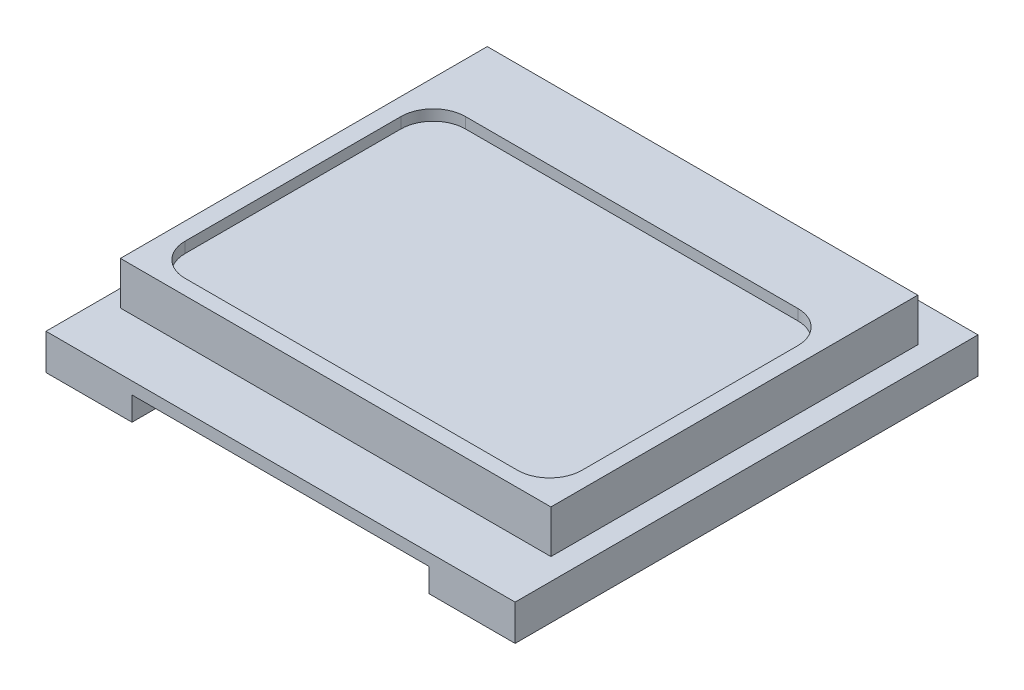
SolidWorks part; units mm, degrees
ref_plane "Front Plane" through (0, 0, 0) normal (0, 0, 1) x (1, 0, 0)
ref_plane "Top Plane" through (0, 0, 0) normal (0, 1, 0) x (1, 0, 0)
ref_plane "Right Plane" through (0, 0, 0) normal (1, 0, 0) x (0, 0, -1)
sketch "Sketch1" plane through (0, 0, 0) normal (0, 1, 0) x (1, 0, 0)
  line L1 (-21.815, 21.525) -> (21.815, 21.525)
  line L2 (-21.815, 21.525) -> (-21.815, -21.525)
  line L3 (-21.815, -21.525) -> (21.815, -21.525)
  line L4 (21.815, 21.525) -> (21.815, -21.525)
  line L5 (-21.815, 21.525) -> (21.815, -21.525) construction
  line L6 (-21.815, -21.525) -> (21.815, 21.525) construction
  point P0 (0, 0)
  dimension "D1" = 43.63
  dimension "D2" = 43.05
extrude "Boss-Extrude1" add sketch "Sketch1" along normal blind 1.13
sketch "Sketch2" plane through (0, 1.13, 0) normal (0, 1, 0) x (1, 0, 0)
  line L0 (0, 21.525) -> (0, 17.925) construction
  line L1 (-20.225, 17.925) -> (19.815, 17.925)
  line L2 (-20.225, 17.925) -> (-20.225, -16.195)
  line L3 (-20.225, -16.195) -> (19.815, -16.195)
  line L4 (19.815, 17.925) -> (19.815, -16.195)
  line L5 (21.815, 21.525) -> (-21.815, 21.525) construction
  line L6 (21.815, 0) -> (19.815, 0) construction
  line L8 (21.815, -21.525) -> (21.815, 21.525) construction
  line L9 (-21.815, 0) -> (-20.225, 0) construction
  line L10 (-21.815, -21.525) -> (21.815, -21.525) construction
  line L11 (0, -21.525) -> (0, -16.195) construction
  line L12 (-21.815, 21.525) -> (-21.815, -21.525) construction
  dimension "D1" = 34.12
  dimension "D2" = 40.04
  dimension "D3" = 3.6
  dimension "D4" = 5.33
  dimension "D5" = 2
  dimension "D6" = 1.59
  dimension "D7" = 5.33
extrude "Boss-Extrude2" add sketch "Sketch2" along normal blind 4
sketch "Sketch4" plane through (0, 5.13, 0) normal (0, 1, 0) x (1, 0, 0)
  line L0 (-0.205, 17.925) -> (-0.205, 11.275) construction
  line L1 (-18.605, 11.275) -> (18.305, 11.275)
  line L2 (-18.605, 11.275) -> (-18.605, -14.795)
  line L3 (-18.605, -14.795) -> (18.305, -14.795)
  line L4 (18.305, 11.275) -> (18.305, -14.795)
  line L6 (19.815, 17.925) -> (-20.225, 17.925) construction
  line L8 (-0.205, -14.795) -> (-0.205, -16.195) construction
  line L9 (-20.225, -16.195) -> (19.815, -16.195) construction
  line L10 (19.815, 0.865) -> (18.305, 0.865) construction
  line L11 (19.815, -16.195) -> (19.815, 17.925) construction
  line L13 (-18.605, 0.865) -> (-20.225, 0.865) construction
  line L14 (-20.225, 17.925) -> (-20.225, -16.195) construction
  dimension "D1" = 1.4
  dimension "D2" = 1.51
  dimension "D3" = 1.62
  dimension "D4" = 6.65
extrude "Cut-Extrude1" cut sketch "Sketch4" against normal blind 1
fillet "Fillet1" radius 3 4 edges at (-18.605, 4.63, 14.795) (18.305, 4.63, 14.795) (-18.605, 4.63, -11.275) (18.305, 4.63, -11.275)
sketch "Sketch5" plane through (0, 0, 0) normal (0, -1, 0) x (1, 0, 0)
  line L0 (21.815, -21.525) -> (-21.815, -21.525) construction
  line L5 (10.5, -21.525) -> (-10.5, -21.525)
  line L6 (10.5, -21.525) -> (10.5, -12.525)
  line L7 (10.5, -12.525) -> (-10.5, -12.525)
  line L8 (-10.5, -21.525) -> (-10.5, -12.525)
  line L9 (21.815, -18.5447) -> (10.5, -18.5447) construction
  line L10 (21.815, 21.525) -> (21.815, -21.525) construction
  line L11 (10.5, -18.5447) -> (-10.5, -18.5447) construction
  line L12 (-10.5, -18.5447) -> (-21.815, -18.5447) construction
  line L13 (-21.815, -21.525) -> (-21.815, 21.525) construction
  dimension "D1" = 21
  dimension "D2" = 9
extrude "Boss-Extrude3" add sketch "Sketch5" along normal blind 10
sketch "Sketch6" plane through (0, 0, 0) normal (0, -1, 0) x (1, 0, 0)
  line L0 (-21.815, 21.525) -> (21.815, 21.525) construction
  line L1 (13.815, -21.525) -> (21.815, -21.525)
  line L2 (21.815, -21.525) -> (21.815, 21.525)
  line L3 (21.815, 21.525) -> (13.815, 21.525)
  line L4 (13.815, -21.525) -> (13.815, 21.525)
  line L6 (-21.815, -21.525) -> (-13.815, -21.525)
  line L7 (-21.815, -21.525) -> (-21.815, 21.525)
  line L8 (-21.815, 21.525) -> (-13.815, 21.525)
  line L9 (-13.815, -21.525) -> (-13.815, 21.525)
  dimension "D1" = 8
extrude "Boss-Extrude4" add sketch "Sketch6" along normal blind 2.2
